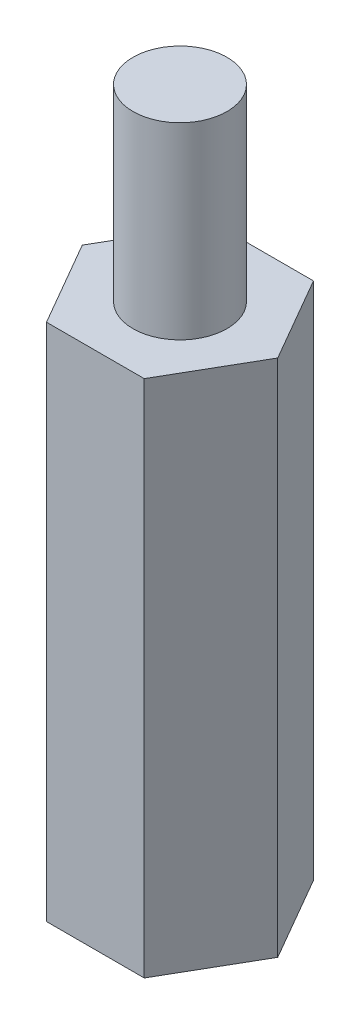
SolidWorks part; units mm, degrees
ref_plane "Alzado" through (0, 0, 0) normal (0, 0, 1) x (1, 0, 0)
ref_plane "Planta" through (0, 0, 0) normal (0, 1, 0) x (1, 0, 0)
ref_plane "Vista lateral" through (0, 0, 0) normal (1, 0, 0) x (0, 0, -1)
sketch "Croquis1" plane through (0, 0, 0) normal (0, 1, 0) x (1, 0, 0)
  line L1 (2.5981, 0) -> (1.299, 2.25)
  line L2 (1.299, 2.25) -> (-1.299, 2.25)
  line L3 (-1.299, 2.25) -> (-2.5981, 0)
  line L4 (-2.5981, 0) -> (-1.299, -2.25)
  line L5 (-1.299, -2.25) -> (1.299, -2.25)
  line L6 (1.299, -2.25) -> (2.5981, 0)
  circle A0 centre (0, 0) radius 2.25 construction
  dimension "D1" = 4.5
extrude "Saliente-Extruir1" add sketch "Croquis1" along normal blind 13.8
sketch "Croquis2" plane through (0, 13.8, 0) normal (0, 1, 0) x (1, 0, 0)
  circle A0 centre (0, 0) radius 1.25
  dimension "D1" = 2.5
extrude "Saliente-Extruir2" add sketch "Croquis2" along normal blind 5
